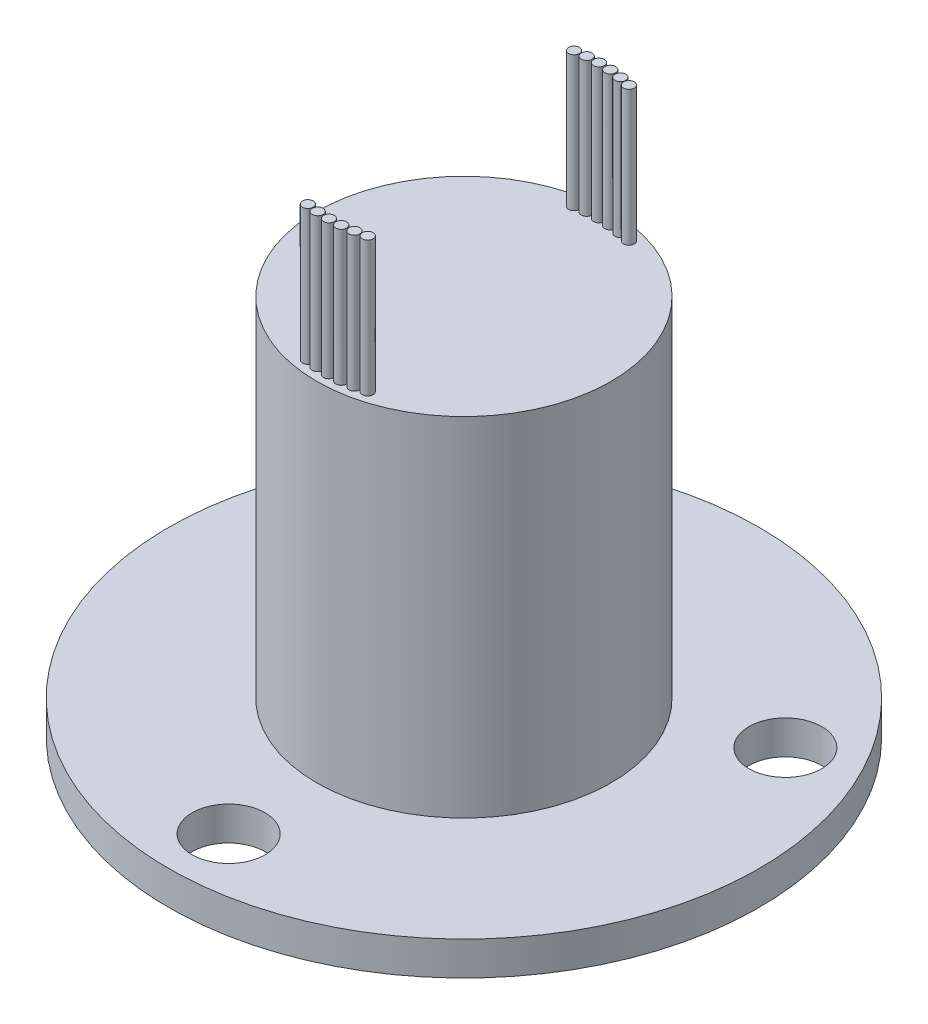
SolidWorks part; units mm, degrees
ref_plane "前视基准面" through (0, 0, 0) normal (0, 0, 1) x (1, 0, 0)
ref_plane "上视基准面" through (0, 0, 0) normal (0, 1, 0) x (1, 0, 0)
ref_plane "右视基准面" through (0, 0, 0) normal (1, 0, 0) x (0, 0, -1)
sketch "草图1" plane through (0, 0, 0) normal (0, 0, 1) x (1, 0, 0)
  line L0 (21.875, 2.5) -> (0, 2.5)
  line L1 (0, 2.5) -> (0, 0)
  line L2 (0, 0) -> (21.875, 0)
  line L3 (21.875, 0) -> (21.875, 2.5)
  line L4 (0, 2.5) -> (0, 0) construction
revolve "旋转1" add sketch "草图1" angle 360 about L4
sketch "草图2" plane through (0, 2.5, 0) normal (0, 1, 0) x (-1, 0, 0)
  circle A0 centre (0, 0) radius 10.9
extrude "凸台-拉伸1" add sketch "草图2" along normal blind 25.75
hole_wizard "M18 间隙孔1" positions "草图4" profile "草图3" hole size "M18" standard "ANSI Metric"
sketch "草图4" plane through (0, 0, 0) normal (0, -1, 0) x (-1, 0, 0)
  point P0 (0, 0)
sketch "草图3" plane through (0, 0, 0) normal (1, 0, 0) x (0, 0, -1)
  line L0 (0, 0) -> (0, 1.6)
  line L1 (0, 1.6) -> (9.6, 1.6)
  line L2 (9.6, 1.6) -> (9.6, 0)
  line L5 (9.6, 0) -> (0, 0)
  line L10 (0, 1.6) -> (-9.6, 1.6) construction
  line L11 (0, -6.35) -> (0, 107.95) construction
  dimension "孔直径" = 19.2
  dimension "孔深度" = 1.6
  dimension "导头角度" = 180
sketch "草图5" plane through (0, 0, 0) normal (0, 0, 1) x (1, 0, 0)
  line L0 (8.1, 1.6) -> (0, 1.6)
  line L1 (0, 1.6) -> (0, 0)
  line L2 (0, 0) -> (8.1, 0)
  line L3 (8.1, 0) -> (8.1, 1.6)
  line L4 (0, 1.6) -> (0, 0) construction
revolve "旋转2" add sketch "草图5" angle 360 about L4
ref_plane "基准面1" through (0, 0, 9.8478) normal (0, 0, 1) x (1, 0, 0)
sketch "草图6" plane through (0, 0, 9.8478) normal (0, 0, 1) x (1, 0, 0)
  line L0 (2.138, 38.25) -> (1.738, 38.25)
  line L1 (1.738, 38.25) -> (1.738, 28.25)
  line L2 (1.738, 28.25) -> (2.138, 28.25)
  line L3 (2.138, 28.25) -> (2.138, 38.25)
  line L4 (1.738, 38.25) -> (1.738, 28.25) construction
revolve "旋转3" add sketch "草图6" angle 360 about L4
ref_plane "基准面2" through (0, 0, 9.8541) normal (0, 0, 1) x (1, 0, 0)
sketch "草图7" plane through (0, 0, 9.8541) normal (0, 0, 1) x (1, 0, 0)
  line L0 (-1.3021, 38.25) -> (-1.7021, 38.25)
  line L1 (-1.7021, 38.25) -> (-1.7021, 28.25)
  line L2 (-1.7021, 28.25) -> (-1.3021, 28.25)
  line L3 (-1.3021, 28.25) -> (-1.3021, 38.25)
  line L4 (-1.7021, 38.25) -> (-1.7021, 28.25) construction
revolve "旋转4" add sketch "草图7" angle 360 about L4
ref_plane "基准面3" through (0, 0, 9.9619) normal (0, 0, 1) x (1, 0, 0)
sketch "草图8" plane through (0, 0, 9.9619) normal (0, 0, 1) x (1, 0, 0)
  line L0 (-0.4716, 38.25) -> (-0.8716, 38.25)
  line L1 (-0.8716, 38.25) -> (-0.8716, 28.25)
  line L2 (-0.8716, 28.25) -> (-0.4716, 28.25)
  line L3 (-0.4716, 28.25) -> (-0.4716, 38.25)
  line L4 (-0.8716, 38.25) -> (-0.8716, 28.25) construction
revolve "旋转5" add sketch "草图8" angle 360 about L4
sketch "草图9" plane through (0, 0, 9.9619) normal (0, 0, 1) x (1, 0, 0)
  line L0 (1.2716, 38.25) -> (0.8716, 38.25)
  line L1 (0.8716, 38.25) -> (0.8716, 28.25)
  line L2 (0.8716, 28.25) -> (1.2716, 28.25)
  line L3 (1.2716, 28.25) -> (1.2716, 38.25)
  line L4 (0.8716, 38.25) -> (0.8716, 28.25) construction
revolve "旋转6" add sketch "草图9" angle 360 about L4
ref_plane "基准面4" through (0, 0, 10) normal (0, 0, 1) x (1, 0, 0)
sketch "草图10" plane through (0, 0, 10) normal (0, 0, 1) x (1, 0, 0)
  line L0 (0.4, 38.25) -> (0, 38.25)
  line L1 (0, 38.25) -> (0, 28.25)
  line L2 (0, 28.25) -> (0.4, 28.25)
  line L3 (0.4, 28.25) -> (0.4, 38.25)
  line L4 (0, 38.25) -> (0, 28.25) construction
revolve "旋转7" add sketch "草图10" angle 360 about L4
ref_plane "基准面5" through (0, 0, -9.671) normal (0, 0, 1) x (1, 0, 0)
sketch "草图11" plane through (0, 0, -9.671) normal (0, 0, 1) x (1, 0, 0)
  line L0 (2.944, 38.25) -> (2.544, 38.25)
  line L1 (2.544, 38.25) -> (2.544, 28.25)
  line L2 (2.544, 28.25) -> (2.944, 28.25)
  line L3 (2.944, 28.25) -> (2.944, 38.25)
  line L4 (2.544, 38.25) -> (2.544, 28.25) construction
revolve "旋转8" add sketch "草图11" angle 360 about L4
ref_plane "基准面6" through (0, 0, -9.8478) normal (0, 0, 1) x (1, 0, 0)
sketch "草图12" plane through (0, 0, -9.8478) normal (0, 0, 1) x (1, 0, 0)
  line L0 (2.138, 38.25) -> (1.738, 38.25)
  line L1 (1.738, 38.25) -> (1.738, 28.25)
  line L2 (1.738, 28.25) -> (2.138, 28.25)
  line L3 (2.138, 28.25) -> (2.138, 38.25)
  line L4 (1.738, 38.25) -> (1.738, 28.25) construction
revolve "旋转9" add sketch "草图12" angle 360 about L4
ref_plane "基准面7" through (0, 0, -9.8541) normal (0, 0, 1) x (1, 0, 0)
sketch "草图13" plane through (0, 0, -9.8541) normal (0, 0, 1) x (1, 0, 0)
  line L0 (-1.3021, 38.25) -> (-1.7021, 38.25)
  line L1 (-1.7021, 38.25) -> (-1.7021, 28.25)
  line L2 (-1.7021, 28.25) -> (-1.3021, 28.25)
  line L3 (-1.3021, 28.25) -> (-1.3021, 38.25)
  line L4 (-1.7021, 38.25) -> (-1.7021, 28.25) construction
revolve "旋转10" add sketch "草图13" angle 360 about L4
ref_plane "基准面8" through (0, 0, -9.9619) normal (0, 0, 1) x (1, 0, 0)
sketch "草图14" plane through (0, 0, -9.9619) normal (0, 0, 1) x (1, 0, 0)
  line L0 (-0.4716, 38.25) -> (-0.8716, 38.25)
  line L1 (-0.8716, 38.25) -> (-0.8716, 28.25)
  line L2 (-0.8716, 28.25) -> (-0.4716, 28.25)
  line L3 (-0.4716, 28.25) -> (-0.4716, 38.25)
  line L4 (-0.8716, 38.25) -> (-0.8716, 28.25) construction
revolve "旋转11" add sketch "草图14" angle 360 about L4
sketch "草图15" plane through (0, 0, -9.9619) normal (0, 0, 1) x (1, 0, 0)
  line L0 (1.2716, 38.25) -> (0.8716, 38.25)
  line L1 (0.8716, 38.25) -> (0.8716, 28.25)
  line L2 (0.8716, 28.25) -> (1.2716, 28.25)
  line L3 (1.2716, 28.25) -> (1.2716, 38.25)
  line L4 (0.8716, 38.25) -> (0.8716, 28.25) construction
revolve "旋转12" add sketch "草图15" angle 360 about L4
ref_plane "基准面9" through (0, 0, -10) normal (0, 0, 1) x (1, 0, 0)
sketch "草图16" plane through (0, 0, -10) normal (0, 0, 1) x (1, 0, 0)
  line L0 (0.4, 38.25) -> (0, 38.25)
  line L1 (0, 38.25) -> (0, 28.25)
  line L2 (0, 28.25) -> (0.4, 28.25)
  line L3 (0.4, 28.25) -> (0.4, 38.25)
  line L4 (0, 38.25) -> (0, 28.25) construction
revolve "旋转13" add sketch "草图16" angle 360 about L4
ref_plane "基准面10" through (0, 0, 9.671) normal (0, 0, 1) x (1, 0, 0)
sketch "草图17" plane through (0, 0, 9.671) normal (0, 0, 1) x (1, 0, 0)
  line L0 (2.944, 38.25) -> (2.544, 38.25)
  line L1 (2.544, 38.25) -> (2.544, 28.25)
  line L2 (2.544, 28.25) -> (2.944, 28.25)
  line L3 (2.944, 28.25) -> (2.944, 38.25)
  line L4 (2.544, 38.25) -> (2.544, 28.25) construction
revolve "旋转14" add sketch "草图17" angle 360 about L4
hole_wizard "Ø5.4 (5.4) 直径孔1" positions "草图19" profile "草图18" hole size "Ø5.4" standard "ANSI Metric"
sketch "草图19" plane through (0, 2.5, 0) normal (0, 1, 0) x (1, 0, 0)
  point P0 (0, -17.425)
  point P1 (-15.0905, 8.7125)
  point P2 (15.0905, 8.7125)
sketch "草图18" plane through (0, 2.5, 17.425) normal (1, 0, 0) x (0, 0, 1)
  line L0 (0, 0) -> (0, 2.5)
  line L1 (0, 2.5) -> (2.7, 2.5)
  line L2 (2.7, 2.5) -> (2.7, 0)
  line L5 (2.7, 0) -> (0, 0)
  line L11 (0, -6.35) -> (0, 107.95) construction
  dimension "通孔孔直径" = 5.4
  dimension "通孔孔深度" = 2.5
hole_wizard "Ø9.5 (9.5) 直径孔1" positions "草图21" profile "草图20" hole size "Ø9.5" standard "ANSI Metric"
sketch "草图21" plane through (0, 0, 0) normal (0, -1, 0) x (-1, 0, 0)
  point P0 (0, 0)
sketch "草图20" plane through (0, 0, 0) normal (1, 0, 0) x (0, 0, -1)
  line L0 (0, 0) -> (0, 0.5)
  line L1 (0, 0.5) -> (4.75, 0.5)
  line L2 (4.75, 0.5) -> (4.75, 0)
  line L5 (4.75, 0) -> (0, 0)
  line L10 (0, 0.5) -> (-4.75, 0.5) construction
  line L11 (0, -6.35) -> (0, 107.95) construction
  dimension "孔直径" = 9.5
  dimension "孔深度" = 0.5
  dimension "导头角度" = 180
